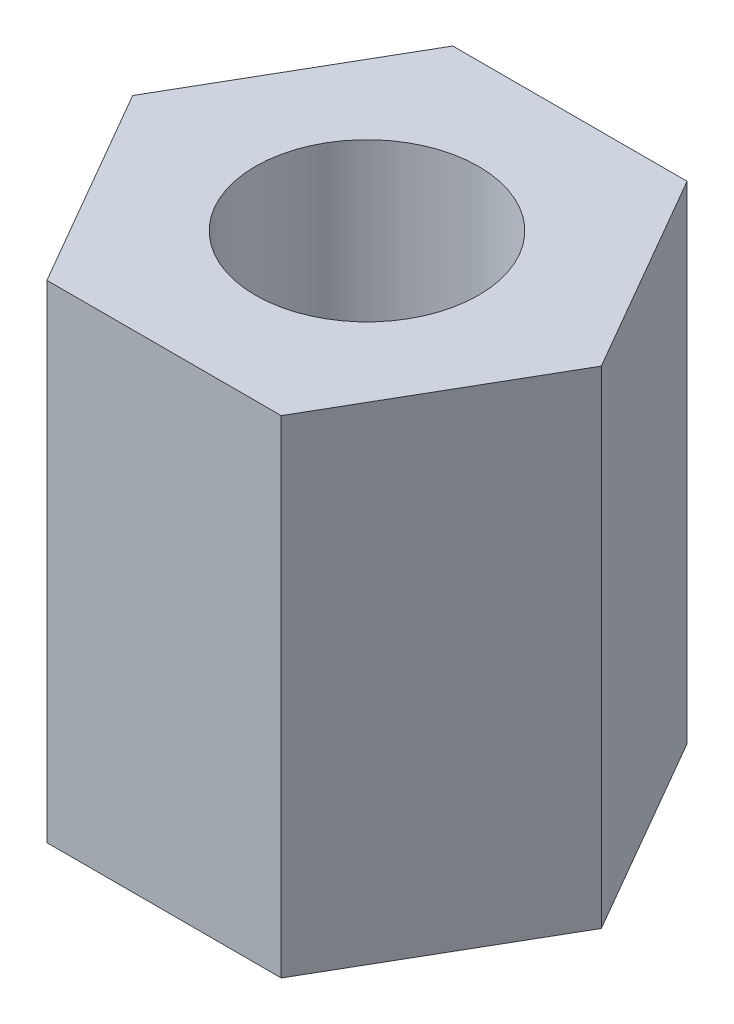
SolidWorks part; units mm, degrees
ref_plane "Front Plane" through (0, 0, 0) normal (0, 0, 1) x (1, 0, 0)
ref_plane "Top Plane" through (0, 0, 0) normal (0, 1, 0) x (1, 0, 0)
ref_plane "Right Plane" through (0, 0, 0) normal (1, 0, 0) x (0, 0, -1)
other "Default"
sketch "Sketch1" plane through (0, 0, 0) normal (0, 1, 0) x (1, 0, 0)
  line L1 (2.8868, 0) -> (1.4434, 2.5)
  line L2 (1.4434, 2.5) -> (-1.4434, 2.5)
  line L3 (-1.4434, 2.5) -> (-2.8868, 0)
  line L4 (-2.8868, 0) -> (-1.4434, -2.5)
  line L5 (-1.4434, -2.5) -> (1.4434, -2.5)
  line L6 (1.4434, -2.5) -> (2.8868, 0)
  circle A0 centre (0, 0) radius 2.5 construction
  circle A1 centre (0, 0) radius 1.375
  dimension "D1" = 2.75
  dimension "D2" = 5
extrude "Boss-Extrude1" add sketch "Sketch1" along normal mid plane 6
